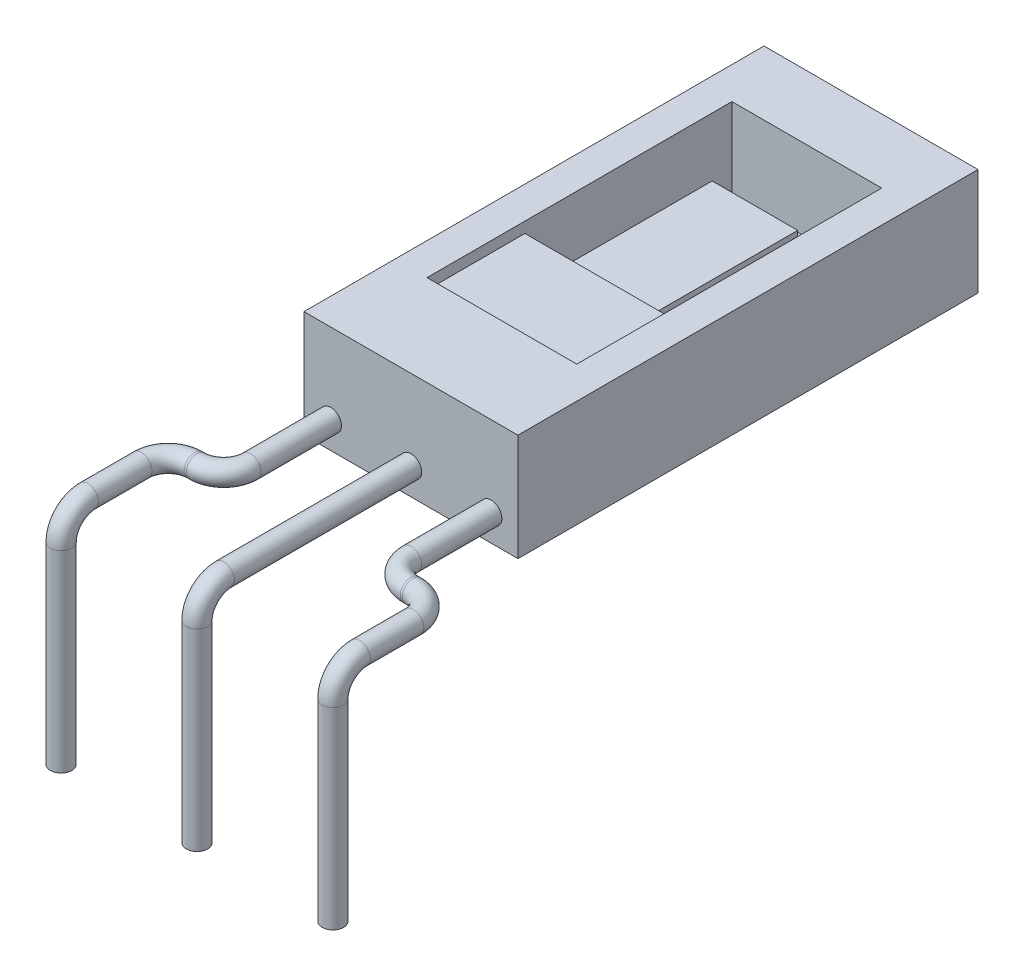
SolidWorks part; units mm, degrees
ref_plane "Plan de face" through (0, 0, 0) normal (0, 0, 1) x (1, 0, 0)
ref_plane "Plan de dessus" through (0, 0, 0) normal (0, 1, 0) x (1, 0, 0)
ref_plane "Plan de droite" through (0, 0, 0) normal (1, 0, 0) x (0, 0, -1)
sketch "Esquisse1" plane through (0, 0, 0) normal (0, 1, 0) x (1, 0, 0)
  line L0 (-6.3491, 0) -> (15.76, 0) construction
  line L1 (2, 11.3549) -> (2, -4.3526) construction
  line L2 (-2, 11.9649) -> (-2, -5.0388) construction
  line L3 (0, -18.8409) -> (0, 14.4626) construction
  line L4 (-6.3491, 8.6) -> (17.6559, 8.6) construction
  line L6 (-2, 8.6) -> (2, 8.6)
  line L7 (-2, 8.6) -> (-2, 0)
  line L8 (-2, 0) -> (2, 0)
  line L9 (2, 8.6) -> (2, 0)
extrude "Extrusion1" add sketch "Esquisse1" along normal blind 2
sketch "Esquisse3" plane through (0, 2, 0) normal (0, 1, 0) x (-1, 0, 0)
  line L0 (2, 0.8724) -> (2, -9.6488) construction
  line L1 (0, -0.411) -> (0, 1.5888) construction
  line L2 (2.4488, -8.6) -> (-2.4014, -8.6) construction
  line L3 (1.4, 0.8724) -> (1.4, -9.6488) construction
  line L4 (2.4488, -1.7) -> (-2.4014, -1.7) construction
  line L5 (2.4488, -7.4) -> (-2.4014, -7.4) construction
  line L6 (-2, 0.8724) -> (-2, -9.6488) construction
  line L7 (-1.4, 0.7381) -> (-1.4, -9.231) construction
  line L9 (1.4, -7.4) -> (-1.4, -7.4)
  line L10 (1.4, -7.4) -> (1.4, -1.7)
  line L11 (1.4, -1.7) -> (-1.4, -1.7)
  line L12 (-1.4, -7.4) -> (-1.4, -1.7)
  dimension "D1" = 0.6
  dimension "D2" = 0.6
  dimension "D3" = 1.2
extrude "Enlèv. mat.-Extru.1" cut sketch "Esquisse3" against normal blind 1.5
sketch "Esquisse4" plane through (0, 0.5, 0) normal (0, 1, 0) x (-1, 0, 0)
  line L0 (3.1801, -1.7) -> (-2.7745, -1.7) construction
  line L1 (-2.7745, -3.53) -> (3.1801, -3.53) construction
  line L3 (1.4, -3.53) -> (-1.4015, -3.53)
  line L4 (1.4, -3.53) -> (1.4, -1.7)
  line L5 (1.4, -1.7) -> (-1.4015, -1.7)
  line L6 (-1.4015, -3.53) -> (-1.4015, -1.7)
  dimension "D1" = 1.83
extrude "Extrusion2" add sketch "Esquisse4" along normal blind 1.3
sketch "Esquisse5" plane through (0, 0.5, 0) normal (0, 1, 0) x (-1, 0, 0)
  line L0 (0, -0.3513) -> (0, -9.0071) construction
  line L1 (-1.7312, -3.53) -> (1.92, -3.53) construction
  line L2 (1.7505, -6.43) -> (-3.3087, -6.43) construction
  line L3 (0.8, -6.873) -> (0.8, -3.0824) construction
  line L4 (-0.8, -6.873) -> (-0.8, -3.0824) construction
  line L6 (0.8, -6.43) -> (-0.8, -6.43)
  line L7 (0.8, -6.43) -> (0.8, -3.53)
  line L8 (0.8, -3.53) -> (-0.8, -3.53)
  line L9 (-0.8, -6.43) -> (-0.8, -3.53)
  dimension "D1" = 2.9
  dimension "D2" = 0.8
  dimension "D3" = 1.6
extrude "Extrusion3" add sketch "Esquisse5" along normal blind 1
sketch "Esquisse6" plane through (0, 0, 0) normal (0, 0, 1) x (1, 0, 0)
  line L0 (0, -0.3461) -> (0, 2.393) construction
  line L1 (-2.4999, 0.5) -> (2.65, 0.5) construction
  circle A0 centre (0, 0.5) radius 0.2
sketch "Esquisse7" plane through (0, 0, 0) normal (1, 0, 0) x (0, 0, -1)
  line L0 (-1.2715, 0) -> (9.5017, 0) construction
  line L1 (-1.2715, -2) -> (9.5017, -2) construction
  line L2 (9.5017, -3.6) -> (-15.0655, -3.6) construction
  line L3 (-7.5586, 0.5) -> (2.1838, 0.5) construction
  line L4 (-4, 1.3427) -> (-4, -4.4933) construction
  line L5 (0, 3.1312) -> (0, -0.9634) construction
  line L6 (0, 0.5) -> (-3.5, 0.5)
  line L7 (-4, 0) -> (-4, -3.6)
  arc A0 (-3.5, 0.5) -> (-4, 0) centre (-3.5, 0) ccw
  dimension "D5" = 0.5
  dimension "D1" = 0.5
  dimension "D2" = 2
  dimension "D3" = 1.6
  dimension "D4" = 4
sweep "Balayage1" add profiles "Esquisse6" path "Esquisse7"
sketch "Esquisse8" plane through (0, 0, 0) normal (0, 0, 1) x (1, 0, 0)
  line L0 (-3.1689, 0) -> (2.5906, 0) construction
  line L1 (2.5906, 0.5) -> (-3.1689, 0.5) construction
  line L2 (0, 2.5696) -> (0, -0.6643) construction
  line L3 (-1.5, 2.5696) -> (-1.5, -0.5581) construction
  circle A0 centre (-1.5, 0.5) radius 0.2
  dimension "D1" = 0.5
  dimension "D2" = 1.5
ref_plane "Plan1" through (0, 0.5, 0) normal (0, 1, 0) x (-1, 0, 0)
sketch "Esquisse10" plane through (0, 0.5, 0) normal (0, 1, 0) x (-1, 0, 0)
  line L0 (0, -1.0237) -> (0, 4.609) construction
  line L1 (1.5, -1.0237) -> (1.5, 4.609) construction
  line L2 (2.8116, 2) -> (0.8473, 2) construction
  line L3 (2.54, 0.9169) -> (2.54, 4.609) construction
  line L4 (2.9252, 4) -> (-2.1408, 4) construction
  line L5 (3.1689, 0) -> (-2.5906, 0) construction
  dimension "D1" = 4
  dimension "D2" = 2
  dimension "D3" = 1.5
  dimension "D4" = 2.54
sketch3d "Esquisse3D3"
  line L1 (-1.5, 0.5, 0) -> (-1.5, 0.5, 1.5)
  line L2 (-2, 0.5, 2) -> (-2.04, 0.5, 2)
  line L3 (-2.54, 0.5, 2.5) -> (-2.54, 0.5, 3.5)
  line L4 (-2.54, 0, 4) -> (-2.54, -3.6, 4)
  arc A0 (-2.54, 0.5, 3.5) -> (-2.54, 0, 4) centre (-2.54, 0, 3.5) ccw
  arc A1 (-2.04, 0.5, 2) -> (-2.54, 0.5, 2.5) centre (-2.04, 0.5, 2.5) ccw
  arc A2 (-1.5, 0.5, 1.5) -> (-2, 0.5, 2) centre (-2, 0.5, 1.5) ccw
  point P8 (-2.54, 0.5, 4)
  point P9 (-2.04, 0, 3.5)
  point P12 (-2.54, 0.5, 2)
  point P13 (-2.04, 1, 2.5)
  point P16 (-1.5, 0.5, 2)
  point P17 (-2, 0, 1.5)
  dimension "D1" = 0.5
  dimension "D2" = 0.5
  dimension "D3" = 0.5
sweep "Balayage2" add profiles "Esquisse8" path "Esquisse3D3"
ref_plane "Plan2" through (0, 0, 0) normal (1, 0, 0) x (0, 0, -1)
mirror "Symétrie1" about plane through (0, 0, 0) normal (1, 0, 0) of "Balayage2"
